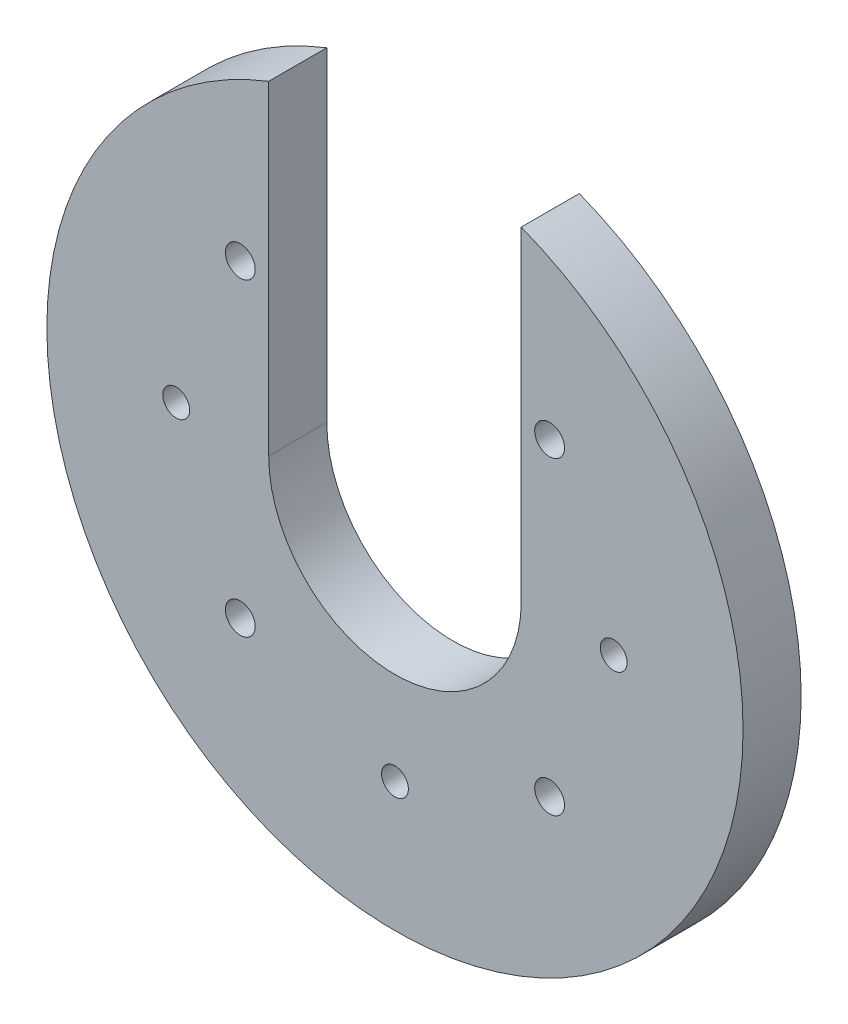
SolidWorks part; units mm, degrees
material "Beech"
ref_plane "Front Plane" through (0, 0, 0) normal (0, 0, 1) x (1, 0, 0)
ref_plane "Top Plane" through (0, 0, 0) normal (0, 1, 0) x (1, 0, 0)
ref_plane "Right Plane" through (0, 0, 0) normal (1, 0, 0) x (0, 0, -1)
sketch "Sketch1" plane through (0, 0, 0) normal (0, 0, 1) x (1, 0, 0)
  line L0 (0, 35.0139) -> (0, -35.0139) construction
  line L1 (-35.0139, 0) -> (35.0139, 0) construction
  line L2 (12.7, 0) -> (22, 0) construction
  line L4 (-12.7, 0) -> (-12.7, 32.6295)
  line L5 (12.7, 0) -> (12.7, 32.6295)
  arc A0 (-12.7, 32.6295) -> (12.7, 32.6295) centre (0, 0) ccw
  arc A1 (-12.7, 0) -> (12.7, 0) centre (0, 0) ccw
  circle A2 centre (22, 0) radius 1.35
  circle A3 centre (0, -22) radius 1.35
  circle A4 centre (-22, 0) radius 1.35
  circle A5 centre (0, 22) radius 1.35 [skipped]
  point P20 (0, 0)
  point P29 (0, 0)
  dimension "D1" = 70.0278
  dimension "D2" = 25.4
  dimension "D4" = 2.7
  dimension "D3" = 22
  dimension "D5" = 4
extrude "Boss-Extrude1" add sketch "Sketch1" along normal blind 5.842
sketch "Sketch2" plane through (0, 0, 5.842) normal (0, 0, 1) x (1, 0, 0)
  line L0 (-15.5563, -15.5563) -> (0, 0) construction
  line L1 (0, 0) -> (0, -22) construction
  circle A0 centre (-15.5563, -15.5563) radius 1.5
  circle A1 centre (-15.5563, 15.5563) radius 1.5
  circle A2 centre (15.5563, 15.5563) radius 1.5
  circle A3 centre (15.5563, -15.5563) radius 1.5
  point P15 (0, 0)
  dimension "D2" = 3
  dimension "D3" = 4
  dimension "D1" = 45
extrude "Cut-Extrude1" cut sketch "Sketch2" against normal through all
